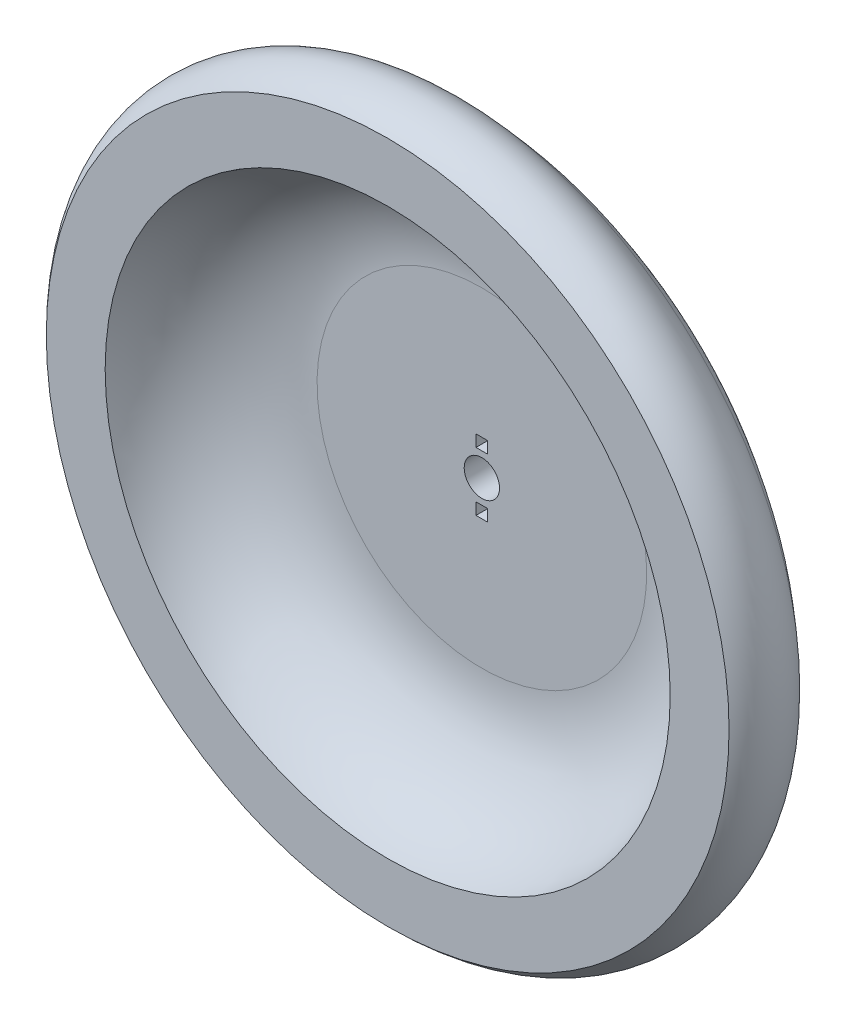
SolidWorks part; units mm, degrees
ref_plane "Front Plane" through (0, 0, 0) normal (0, 0, 1) x (1, 0, 0)
ref_plane "Top Plane" through (0, 0, 0) normal (0, 1, 0) x (1, 0, 0)
ref_plane "Right Plane" through (0, 0, 0) normal (1, 0, 0) x (0, 0, -1)
sketch "Sketch1" plane through (0, 0, 0) normal (1, 0, 0) x (0, 0, -1)
  line L1 (15, 0) -> (15, 14)
  line L4 (15, 0) -> (11, 0)
  line L5 (3, 24) -> (3, 29)
  line L6 (11, 14) -> (11, 0)
  line L7 (11, 0) -> (3, 0) construction
  line L8 (3, 0) -> (3, 24) construction
  arc A1 (15, 14) -> (9, 29) centre (-6.75, 14) ccw
  arc A2 (9, 29) -> (3, 29) centre (6, 26.1429) ccw
  arc A3 (3, 24) -> (11, 14) centre (0.75, 14) cw
  point P12 (0, 0)
  point P14 (0, 0)
  point P15 (10, 0)
  dimension "D3" = 14
  dimension "D1" = 29
  dimension "D2" = 15
  dimension "D4" = 3
  dimension "D5" = 4
  dimension "D6" = 5
  dimension "D7" = 12
revolve "Revolve1" add sketch "Sketch1" angle 360 about L4
hole_wizard "Ø3.0mm Dowel Hole1" positions "3DSketch1" profile "Sketch2" hole size "Ø3.0" standard "ANSI Metric" end condition through all
sketch3d "3DSketch1"
  point P0 (0, 0, 0)
  point P3 (0, 0, 0)
  point P5 (0, 0, -15)
sketch "Sketch2" plane through (0, 0, -15) normal (1, 0, 0) x (0, 1, 0)
  line L0 (0, 0) -> (0, 12)
  line L1 (0, 12) -> (1.5, 12)
  line L2 (1.5, 12) -> (1.5, 0)
  line L5 (1.5, 0) -> (0, 0)
  line L11 (0, -6.35) -> (0, 107.95) construction
  dimension "Thru Hole Dia." = 3
  dimension "Thru Hole Depth" = 12
sketch "Sketch5" plane through (0, 0, -11) normal (0, 0, 1) x (1, 0, 0)
  line L0 (0, 3.5) -> (0, -3.5) construction
  line L1 (-0.5, 3) -> (0.5, 3)
  line L2 (-0.5, 3) -> (-0.5, 2)
  line L3 (-0.5, 2) -> (0.5, 2)
  line L4 (0.5, 3) -> (0.5, 2)
  line L5 (-0.5, -2) -> (0.5, -2)
  line L6 (-0.5, -2) -> (-0.5, -3)
  line L7 (-0.5, -3) -> (0.5, -3)
  line L8 (0.5, -2) -> (0.5, -3)
  circle A0 centre (0, 0) radius 3.5 construction
  circle A1 centre (0, 0) radius 2.5 construction
  point P13 (0, 2)
  point P14 (0, -2)
  point P16 (0, 2.5)
  point P17 (0, -2.5)
  point P18 (0.5, -2.5)
  point P19 (0.5, 2.5)
  dimension "D1" = 7
  dimension "D3" = 5
  dimension "D2" = 1
extrude "Axial_Transmision" cut sketch "Sketch5" against normal blind 2
